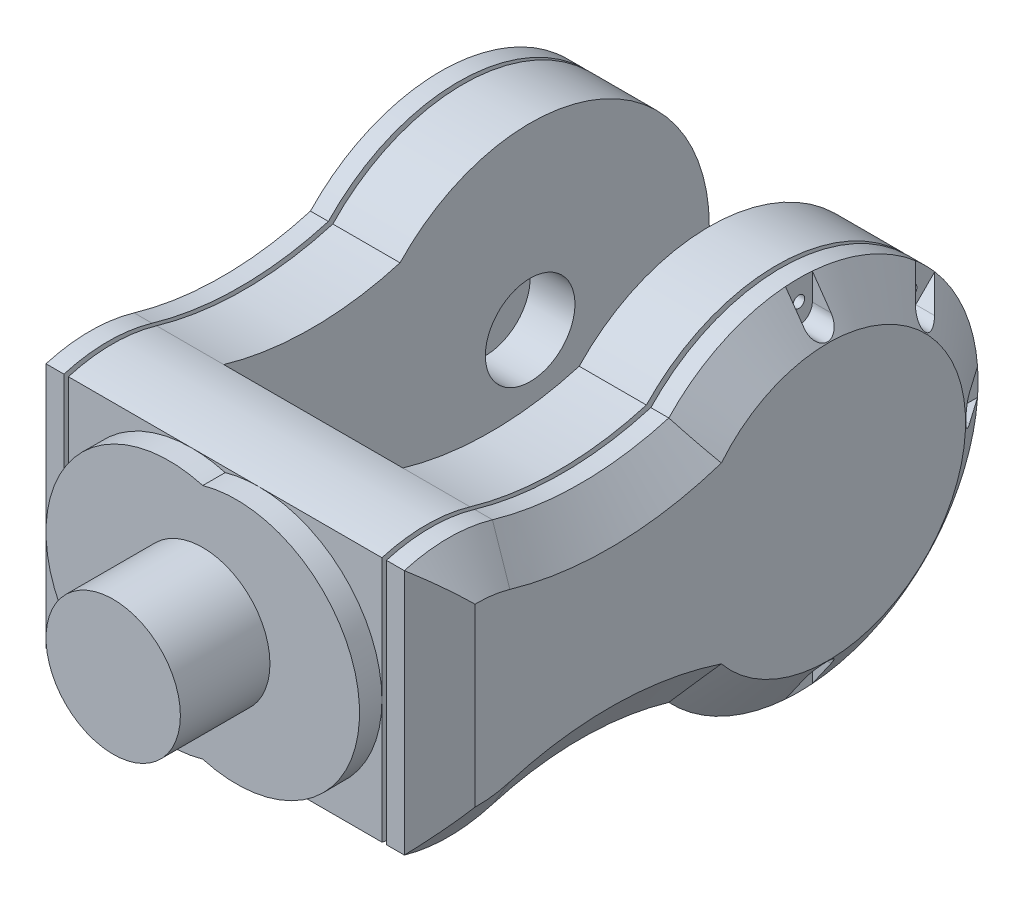
SolidWorks part; units mm, degrees
ref_plane "Ön Düzlem" through (0, 0, 0) normal (0, 0, 1) x (1, 0, 0)
ref_plane "Üst Düzlem" through (0, 0, 0) normal (0, 1, 0) x (1, 0, 0)
ref_plane "Sağ Düzlem" through (0, 0, 0) normal (1, 0, 0) x (0, 0, -1)
sketch "Çizim2" plane through (0, 0, 0) normal (0, 0, 1) x (1, 0, 0)
  circle A0 centre (0, 0) radius 27.5
extrude "Yükseklik-Ekstrüzyon1" add sketch "Çizim2" along normal blind 5
ref_plane "Düzlem1" through (27.5, 0, 0) normal (1, 0, 0) x (0, 0, -1)
sketch "Çizim3" plane through (27.5, 0, 0) normal (1, 0, 0) x (0, 0, -1)
  line L0 (0, 0) -> (-21.9096, 0) construction
  line L1 (0, 27.5) -> (0, -27.5)
  arc A1 (0, 27.5) -> (19.681, 27.5) centre (9.8405, -6.0882) cw
  arc A2 (19.681, 27.5) -> (59.043, 27.5) centre (39.362, 94.6763) ccw
  arc A3 (0, -27.5) -> (19.681, -27.5) centre (9.8405, 6.0882) ccw
  arc A4 (19.681, -27.5) -> (59.043, -27.5) centre (39.362, -94.6763) cw
  arc A5 (59.043, -27.5) -> (59.043, 27.5) centre (88.0904, 0) ccw
  dimension "D2" = 110
  dimension "D3" = 35
  dimension "D1" = 80
extrude "Yükseklik-Ekstrüzyon2" add sketch "Çizim3" along normal blind 15 separate body
sketch "Çizim4" plane through (42.5, 0, 0) normal (1, 0, 0) x (0, 0, -1)
  line L2 (2.5, 25.572) -> (2.5, -25.572)
  line L3 (2.5, 25.572) -> (2.5, -25.572)
  arc A28 (2.5, -25.572) -> (18.9781, -25.1008) centre (9.8405, 6.0882) ccw
  arc A29 (60.4097, -25.2988) -> (18.9781, -25.1008) centre (39.362, -94.6763) ccw
  arc A30 (60.4097, -25.2988) -> (60.4097, 25.2988) centre (88.0904, 0) ccw
  arc A31 (18.9781, 25.1008) -> (60.4097, 25.2988) centre (39.362, 94.6763) ccw
  arc A32 (18.9781, 25.1008) -> (2.5, 25.572) centre (9.8405, -6.0882) ccw
  arc A33 (2.5, -25.572) -> (18.9781, -25.1008) centre (9.8405, 6.0882) ccw
  arc A34 (60.4097, -25.2988) -> (18.9781, -25.1008) centre (39.362, -94.6763) ccw
  arc A35 (60.4097, -25.2988) -> (60.4097, 25.2988) centre (88.0904, 0) ccw
  arc A36 (18.9781, 25.1008) -> (60.4097, 25.2988) centre (39.362, 94.6763) ccw
  arc A37 (18.9781, 25.1008) -> (2.5, 25.572) centre (9.8405, -6.0882) ccw
  dimension "D1" = 2.5
extrude "Yükseklik-Ekstrüzyon3" add sketch "Çizim4" along normal blind 1
sketch "Çizim5" plane through (43.5, 0, 0) normal (1, 0, 0) x (0, 0, -1)
  line L1 (0, 27.5) -> (0, -27.5)
  line L2 (0, 27.5) -> (0, -27.5)
  arc A5 (19.681, 27.5) -> (0, 27.5) centre (9.8405, -6.0882) ccw
  arc A6 (0, -27.5) -> (19.681, -27.5) centre (9.8405, 6.0882) ccw
  arc A7 (59.043, -27.5) -> (19.681, -27.5) centre (39.362, -94.6763) ccw
  arc A8 (59.043, -27.5) -> (59.043, 27.5) centre (88.0904, 0) ccw
  arc A9 (19.681, 27.5) -> (59.043, 27.5) centre (39.362, 94.6763) ccw
  arc A10 (19.681, 27.5) -> (0, 27.5) centre (9.8405, -6.0882) ccw
  arc A11 (0, -27.5) -> (19.681, -27.5) centre (9.8405, 6.0882) ccw
  arc A12 (59.043, -27.5) -> (19.681, -27.5) centre (39.362, -94.6763) ccw
  arc A13 (59.043, -27.5) -> (59.043, 27.5) centre (88.0904, 0) ccw
  arc A14 (19.681, 27.5) -> (59.043, 27.5) centre (39.362, 94.6763) ccw
  dimension "D1" = 0
extrude "Yükseklik-Ekstrüzyon4" add sketch "Çizim5" along normal blind 4
sketch "Çizim6" plane through (47.5, 0, 0) normal (1, 0, 0) x (0, 0, -1)
  line L1 (0, 27.5) -> (0, -27.5)
  line L2 (0, 27.5) -> (0, -27.5)
  arc A5 (19.681, 27.5) -> (59.043, 27.5) centre (39.362, 94.6763) ccw
  arc A6 (19.681, 27.5) -> (0, 27.5) centre (9.8405, -6.0882) ccw
  arc A7 (0, -27.5) -> (19.681, -27.5) centre (9.8405, 6.0882) ccw
  arc A8 (59.043, -27.5) -> (19.681, -27.5) centre (39.362, -94.6763) ccw
  arc A9 (59.043, -27.5) -> (59.043, 27.5) centre (88.0904, 0) ccw
  arc A10 (19.681, 27.5) -> (59.043, 27.5) centre (39.362, 94.6763) ccw
  arc A11 (19.681, 27.5) -> (0, 27.5) centre (9.8405, -6.0882) ccw
  arc A12 (0, -27.5) -> (19.681, -27.5) centre (9.8405, 6.0882) ccw
  arc A13 (59.043, -27.5) -> (19.681, -27.5) centre (39.362, -94.6763) ccw
  arc A14 (59.043, -27.5) -> (59.043, 27.5) centre (88.0904, 0) ccw
  dimension "D1" = 0
extrude "Yükseklik-Ekstrüzyon5" add sketch "Çizim6" along normal blind 6.5 draft 55
sketch "Çizim7" plane through (54, 0, 0) normal (1, 0, 0) x (0, 0, -1)
  line L0 (0, 0) -> (128.0904, 0) construction
  line L1 (127.9778, 3) -> (121.9778, 3)
  line L2 (127.9778, -3) -> (121.9778, -3)
  arc A0 (59.043, -27.5) -> (59.043, 27.5) centre (88.0904, 0) ccw construction
  arc A1 (121.9778, 3) -> (121.9778, -3) centre (121.9778, 0) ccw
  arc A2 (127.9778, 3) -> (127.9778, -3) centre (123.9778, 0) cw
  dimension "D2" = 3
  dimension "D3" = 5
  dimension "D1" = 6
extrude "Kes-Ekstrüzyon1" cut sketch "Çizim7" against normal blind 6.5
sketch "Çizim8" plane through (47.5, 0, 0) normal (1, 0, 0) x (0, 0, -1)
  line L0 (118.9778, 0) -> (128.0904, 0) construction
  arc A0 (121.9778, 3) -> (121.9778, -3) centre (121.9778, 0) ccw construction
  arc A1 (127.9778, -3) -> (127.9778, 3) centre (88.0904, 0) ccw construction
  circle A2 centre (123.5341, 0) radius 1.2887
extrude "Kes-Ekstrüzyon2" cut sketch "Çizim8" against normal blind 5
pattern_circular "Dairesel Kaplama1" count 3 every 45 about axis through (0, 0, -88.0904) along (1, 0, 0) of "Kes-Ekstrüzyon2", "Kes-Ekstrüzyon1"
sketch "Çizim9" plane through (27.5, 0, 0) normal (-1, 0, 0) x (0, 0, 1)
  line L0 (-19.681, 27.5) -> (-19.681, -27.5)
  line L2 (0, -27.5) -> (0, 27.5)
  line L3 (0, -27.5) -> (0, 27.5)
  arc A5 (0, 27.5) -> (-19.681, 27.5) centre (-9.8405, -6.0882) ccw
  arc A6 (-59.043, 27.5) -> (-19.681, 27.5) centre (-39.362, 94.6763) ccw
  arc A7 (-59.043, 27.5) -> (-59.043, -27.5) centre (-88.0904, 0) ccw
  arc A8 (-19.681, -27.5) -> (-59.043, -27.5) centre (-39.362, -94.6763) ccw
  arc A9 (-19.681, -27.5) -> (0, -27.5) centre (-9.8405, 6.0882) ccw
  arc A10 (0, 27.5) -> (-19.681, 27.5) centre (-9.8405, -6.0882) ccw
  arc A14 (-19.681, -27.5) -> (0, -27.5) centre (-9.8405, 6.0882) ccw
  dimension "D1" = 0
extrude "Yükseklik-Ekstrüzyon6" add sketch "Çizim9" along normal blind 40
ref_plane "Düzlem2" through (7.5, 0, 0) normal (-1, 0, 0) x (0, 0, 1)
mirror "Aynalama1" about plane through (7.5, 0, 0) normal (-1, 0, 0) of bodies 109
sketch "Çizim11" plane through (0, 0, 5) normal (0, 0, 1) x (1, 0, 0)
  line L0 (7.5, 26.4575) -> (7.5, -27.5) construction
  line L1 (0, -27.5) -> (15, -27.5) construction
  circle A0 centre (7.5, -0.5212) radius 15
  dimension "D1" = 30
extrude "Yükseklik-Ekstrüzyon7" add sketch "Çizim11" along normal blind 20
sketch "Çizim14" plane through (27.5, 0, 0) normal (-1, 0, 0) x (0, 0, 1)
  circle A0 centre (-88.0904, 0) radius 10
  dimension "D1" = 20
extrude "Kes-Ekstrüzyon4" cut sketch "Çizim14" against normal blind 10
mirror "Aynalama2" about plane through (7.5, 0, 0) normal (-1, 0, 0) of "Kes-Ekstrüzyon4"
